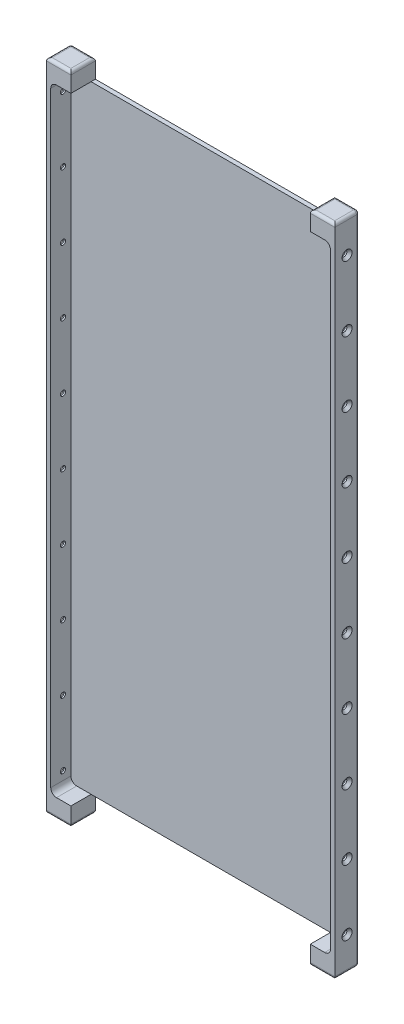
SolidWorks part; units mm, degrees
ref_plane "Front Plane" through (0, 0, 0) normal (0, 0, 1) x (1, 0, 0)
ref_plane "Top Plane" through (0, 0, 0) normal (0, 1, 0) x (1, 0, 0)
ref_plane "Right Plane" through (0, 0, 0) normal (1, 0, 0) x (0, 0, -1)
sketch "Sketch1" plane through (0, 0, 0) normal (0, 0, 1) x (1, 0, 0)
  line L0 (0, 107) -> (0, -107) construction
  line L1 (-41.5, -107) -> (41.5, -107)
  line L2 (-50, -107) -> (-50, 107)
  line L3 (-41.5, 107) -> (41.5, 107)
  line L4 (50, -107) -> (50, 107)
  line L5 (-50, -107) -> (50, 107) construction
  line L6 (-50, 107) -> (50, -107) construction
  line L7 (-50, 0) -> (50, 0) construction
  line L8 (-50, 107) -> (-50, 113.5)
  line L9 (-50, 113.5) -> (-41.5, 113.5)
  line L10 (-41.5, 107) -> (-41.5, 113.5)
  line L12 (50, 107) -> (50, 113.5)
  line L13 (50, 113.5) -> (41.5, 113.5)
  line L14 (41.5, 107) -> (41.5, 113.5)
  line L16 (50, -107) -> (50, -113.5)
  line L17 (50, -113.5) -> (41.5, -113.5)
  line L18 (41.5, -107) -> (41.5, -113.5)
  line L20 (-50, -107) -> (-50, -113.5)
  line L21 (-50, -113.5) -> (-41.5, -113.5)
  line L22 (-41.5, -107) -> (-41.5, -113.5)
  point P0 (0, 0)
  dimension "D1" = 100
  dimension "D2" = 227
  dimension "D3" = 8.5
  dimension "D4" = 6.5
extrude "Boss-Extrude1" add sketch "Sketch1" along normal blind 8.5
fillet "Fillet1" radius 1 18 edges at (41.5, -113.5, 4.25) (45.75, -113.5, 8.5) (50, -113.5, 4.25) (45.75, -113.5, 0) (-50, -113.5, 4.25) (-45.75, -113.5, 8.5) (-41.5, -113.5, 4.25) (-45.75, -113.5, 0) (-41.5, 113.5, 4.25) (-45.75, 113.5, 8.5) (-50, 113.5, 4.25) (-45.75, 113.5, 0) (41.5, 113.5, 4.25) (45.75, 113.5, 8.5) (50, 113.5, 4.25) (45.75, 113.5, 0) (-50, 0, 0) (50, 0, 0)
sketch "Sketch2" plane through (0, 0, 8.5) normal (0, 0, 1) x (1, 0, 0)
  line L1 (-41.5, 107) -> (41.5, 107)
  line L2 (-41.5, 107) -> (-41.5, -107)
  line L3 (-41.5, -107) -> (41.5, -107)
  line L4 (41.5, 107) -> (41.5, -107)
extrude "Cut-Extrude1" cut sketch "Sketch2" against normal blind 7
sketch "Sketch3" plane through (0, 0, 8.5) normal (0, 0, 1) x (1, 0, 0)
  line L0 (-50, 112.5) -> (-50, -112.5) construction
  line L1 (-48.5, 107) -> (48.5, 107)
  line L2 (-48.5, 107) -> (-48.5, -107)
  line L3 (-48.5, -107) -> (48.5, -107)
  line L4 (48.5, 107) -> (48.5, -107)
  line L5 (50, -112.5) -> (50, 112.5) construction
  line L6 (41.5, 107) -> (-41.5, 107) construction
  line L7 (-41.5, -107) -> (41.5, -107) construction
  dimension "D1" = 1.5
  dimension "D2" = 1.5
extrude "Cut-Extrude2" cut sketch "Sketch3" against normal up to surface (7 mm away) up to face at (0, 0, 1.5)
fillet "Fillet2" radius 2 4 edges at (48.5, -107, 5) (-48.5, -107, 5) (-48.5, 107, 5) (48.5, 107, 5)
hole_wizard "CSK for #0 Flat Head Machine Screw1" positions "Sketch5" profile "Sketch4" countersink size "#0" standard "ANSI Inch"
sketch "Sketch5" plane through (-50, 0, 0) normal (-1, 0, 0) x (0, 0, 1)
  line L0 (8.5, 112.5) -> (8.5, -112.5) construction
  point P0 (4.25, 102)
  point P17 (4.25, 79.3333)
  point P18 (4.25, 56.6667)
  point P19 (4.25, 34)
  point P20 (4.25, 11.3333)
  point P21 (4.25, -11.3333)
  point P22 (4.25, -34)
  point P23 (4.25, -56.6667)
  point P24 (4.25, -79.3333)
  point P25 (4.25, -102)
  dimension "D1" = 5
  dimension "D2" = 4.25
  dimension "D4" = 5
  dimension "D5" = 22.6667
  dimension "D3" = 10
sketch "Sketch4" plane through (-50, 102, 4.25) normal (0, 1, 0) x (0, 0, 1)
  line L0 (0, 0) -> (0, 3.8362)
  line L1 (0, 3.8362) -> (0.889, 3.302)
  line L2 (0.889, 3.302) -> (0.889, 0.9699)
  line L3 (0.889, 0.9699) -> (1.7321, 0)
  line L5 (1.7321, 0) -> (0, 0)
  line L6 (-0.889, 0.9699) -> (-1.7321, 0) construction
  line L10 (0, 3.8362) -> (-0.889, 3.302) construction
  line L11 (0, -6.35) -> (0, 107.95) construction
  dimension "Hole Dia." = 1.778
  dimension "Hole Depth" = 3.302
  dimension "Near C'Sink Dia." = 3.4642
  dimension "Near C'Sink Angle" = 82
  dimension "Drill Angle" = 118
mirror "Mirror1" about plane through (0, 0, 0) normal (1, 0, 0) of "CSK for #0 Flat Head Machine Screw1"
